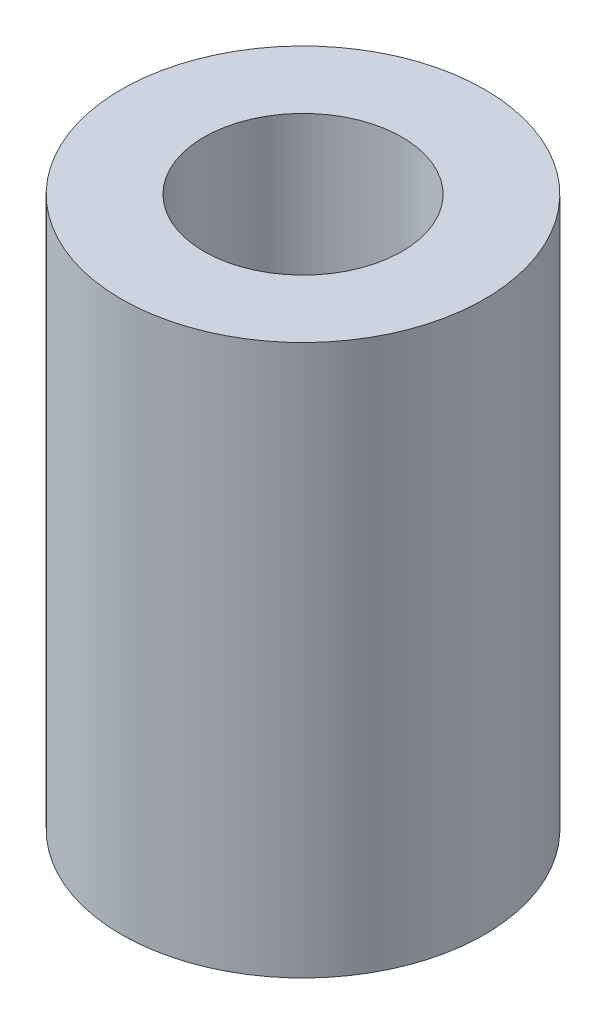
SolidWorks part; units mm, degrees
ref_plane "Front Plane" through (0, 0, 0) normal (0, 0, 1) x (1, 0, 0)
ref_plane "Top Plane" through (0, 0, 0) normal (0, 1, 0) x (1, 0, 0)
ref_plane "Right Plane" through (0, 0, 0) normal (1, 0, 0) x (0, 0, -1)
sketch "Sketch1" plane through (0, 0, 0) normal (0, 1, 0) x (1, 0, 0)
  circle A0 centre (0, 0) radius 1.8
  circle A1 centre (0, 0) radius 3.3
  dimension "D1" = 3.6
  dimension "D2" = 1.5
extrude "Boss-Extrude1" add sketch "Sketch1" along normal blind 10
